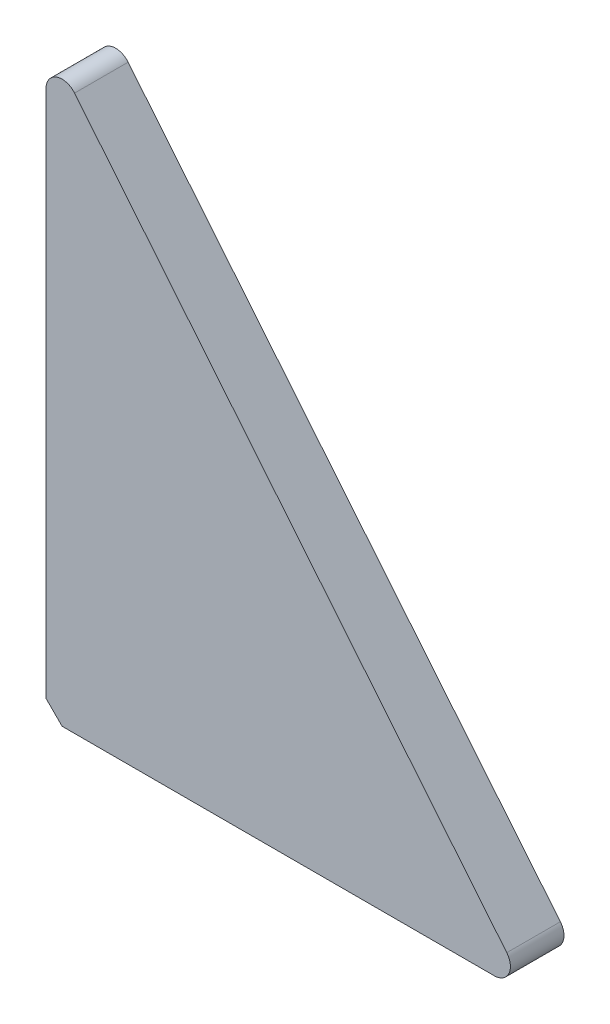
SolidWorks part; units mm, degrees
ref_plane "Ön Düzlem" through (0, 0, 0) normal (0, 0, 1) x (1, 0, 0)
ref_plane "Üst Düzlem" through (0, 0, 0) normal (0, 1, 0) x (1, 0, 0)
ref_plane "Sağ Düzlem" through (0, 0, 0) normal (1, 0, 0) x (0, 0, -1)
sketch "Çizim1" plane through (0, 0, 0) normal (0, 0, 1) x (1, 0, 0)
  line L0 (0, 0) -> (0, 110)
  line L1 (0, 110) -> (90, 0)
  line L2 (90, 0) -> (0, 0)
  dimension "D1" = 110
  dimension "D2" = 90
extrude "Yükseklik-Ekstrüzyon1" add sketch "Çizim1" along normal blind 10
chamfer "Pah1" distance 3 angle 45 1 edges at (0, 0, 5)
fillet "Radyus1" radius 3 2 edges at (90, 0, 5) (0, 110, 5)
